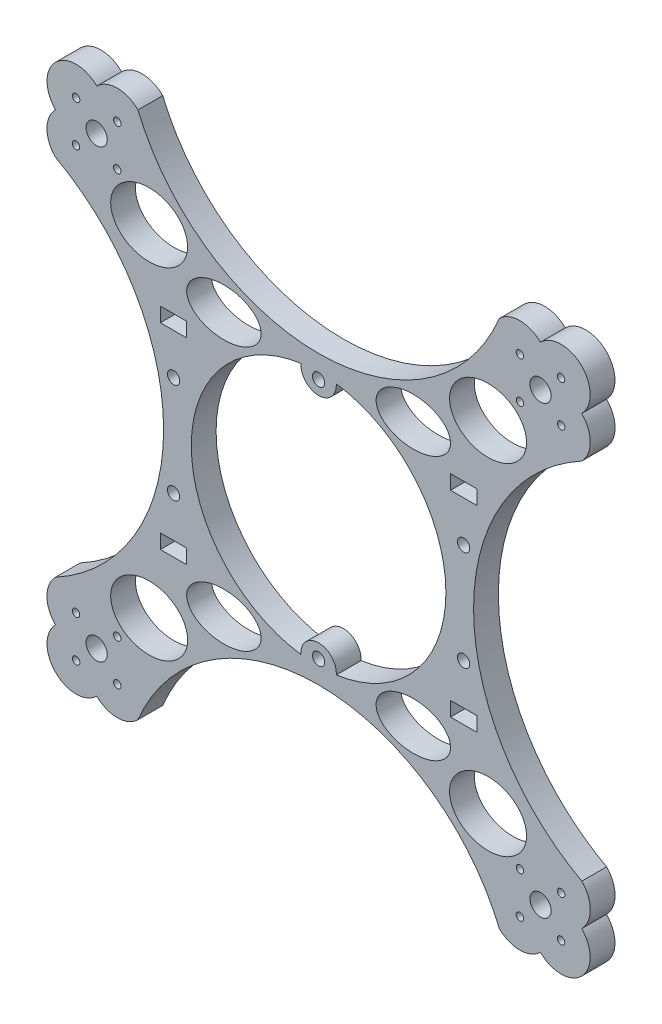
SolidWorks part; units mm, degrees
ref_plane "Front Plane" through (0, 0, 0) normal (0, 0, 1) x (1, 0, 0)
ref_plane "Top Plane" through (0, 0, 0) normal (0, 1, 0) x (1, 0, 0)
ref_plane "Right Plane" through (0, 0, 0) normal (1, 0, 0) x (0, 0, -1)
sketch "Sketch1" plane through (0, 0, 0) normal (0, 0, 1) x (1, 0, 0)
  line L0 (648.4625, 450.3527) -> (648.4625, 50450.3527) construction
  line L1 (648.4625, 450.3527) -> (-34623.3591, 35889.0124) construction
  line L2 (591.254, 498.0985) -> (586.3875, 493.2548) construction
  line L3 (600.9872, 507.7858) -> (605.8538, 512.6295) construction
  line L4 (591.277, 507.8087) -> (596.1435, 512.6524) construction
  line L5 (591.277, 507.8087) -> (586.4104, 502.9651) construction
  line L6 (596.1206, 502.9421) -> (600.9643, 498.0756) construction
  line L7 (596.1206, 502.9421) -> (591.254, 498.0985) construction
  line L8 (596.1206, 502.9421) -> (591.277, 507.8087) construction
  line L9 (596.1206, 502.9421) -> (600.9872, 507.7858) construction
  line L10 (617.3488, 471.8132) -> (617.3488, 475.2133)
  line L11 (611.1488, 471.8132) -> (617.3488, 471.8132)
  line L12 (611.1488, 475.2133) -> (611.1488, 471.8132)
  line L13 (617.3488, 475.2133) -> (611.1488, 475.2133)
  line L14 (617.3488, 471.8132) -> (617.3488, 475.2133)
  line L15 (611.1488, 471.8132) -> (617.3488, 471.8132)
  line L16 (611.1488, 475.2133) -> (611.1488, 471.8132)
  line L17 (617.3488, 475.2133) -> (611.1488, 475.2133)
  line L18 (679.5762, 475.2133) -> (685.7762, 475.2133)
  line L19 (685.7762, 475.2133) -> (685.7762, 471.8132)
  line L20 (685.7762, 471.8132) -> (679.5762, 471.8132)
  line L21 (679.5762, 471.8132) -> (679.5762, 475.2133)
  line L22 (679.5762, 475.2133) -> (685.7762, 475.2133)
  line L23 (685.7762, 475.2133) -> (685.7762, 471.8132)
  line L24 (685.7762, 471.8132) -> (679.5762, 471.8132)
  line L25 (679.5762, 471.8132) -> (679.5762, 475.2133)
  line L26 (705.6709, 402.6069) -> (710.5375, 407.4506) construction
  line L27 (695.9378, 392.9196) -> (691.0712, 388.0759) construction
  line L28 (705.648, 392.8967) -> (700.7814, 388.053) construction
  line L29 (705.648, 392.8967) -> (710.5146, 397.7404) construction
  line L30 (700.8043, 397.7633) -> (695.9607, 402.6299) construction
  line L31 (700.8043, 397.7633) -> (705.6709, 402.6069) construction
  line L32 (700.8043, 502.9421) -> (695.9378, 507.7858) construction
  line L33 (648.4625, 450.3527) -> (35920.2841, 35889.0124) construction
  line L34 (700.8043, 502.9421) -> (705.648, 507.8087) construction
  line L35 (700.8043, 502.9421) -> (705.6709, 498.0985) construction
  line L36 (-351.5375, 450.3527) -> (49648.4625, 450.3527) construction
  line L37 (700.8043, 397.7633) -> (705.648, 392.8967) construction
  line L38 (700.8043, 502.9421) -> (695.9607, 498.0756) construction
  line L39 (705.648, 507.8087) -> (710.5146, 502.9651) construction
  line L40 (705.648, 507.8087) -> (700.7814, 512.6524) construction
  line L41 (695.9378, 507.7858) -> (691.0712, 512.6295) construction
  line L42 (705.6709, 498.0985) -> (710.5375, 493.2548) construction
  line L43 (700.8043, 397.7633) -> (695.9378, 392.9196) construction
  line L44 (596.1206, 397.7633) -> (600.9872, 392.9196) construction
  line L45 (596.1206, 397.7633) -> (591.277, 392.8967) construction
  line L46 (596.1206, 397.7633) -> (591.254, 402.6069) construction
  line L47 (596.1206, 397.7633) -> (600.9643, 402.6299) construction
  line L48 (591.277, 392.8967) -> (586.4104, 397.7404) construction
  line L49 (591.277, 392.8967) -> (596.1435, 388.053) construction
  line L50 (600.9872, 392.9196) -> (605.8538, 388.0759) construction
  line L51 (591.254, 402.6069) -> (586.3875, 407.4506) construction
  line L52 (679.5762, 428.8922) -> (679.5762, 425.4922)
  line L53 (685.7762, 428.8922) -> (679.5762, 428.8922)
  line L54 (685.7762, 425.4922) -> (685.7762, 428.8922)
  line L55 (679.5762, 425.4922) -> (685.7762, 425.4922)
  line L56 (679.5762, 428.8922) -> (679.5762, 425.4922)
  line L57 (685.7762, 428.8922) -> (679.5762, 428.8922)
  line L58 (685.7762, 425.4922) -> (685.7762, 428.8922)
  line L59 (679.5762, 425.4922) -> (685.7762, 425.4922)
  line L60 (617.3488, 425.4922) -> (611.1488, 425.4922)
  line L61 (611.1488, 425.4922) -> (611.1488, 428.8922)
  line L62 (611.1488, 428.8922) -> (617.3488, 428.8922)
  line L63 (617.3488, 428.8922) -> (617.3488, 425.4922)
  line L64 (617.3488, 425.4922) -> (611.1488, 425.4922)
  line L65 (611.1488, 425.4922) -> (611.1488, 428.8922)
  line L66 (611.1488, 428.8922) -> (617.3488, 428.8922)
  line L67 (617.3488, 428.8922) -> (617.3488, 425.4922)
  arc A0 (652.6297, 480.0867) -> (678.487, 450.3527) centre (648.4625, 450.3527) cw
  circle A1 centre (648.4625, 478.8805) radius 1.4499
  arc A2 (586.3875, 493.2548) -> (586.3875, 407.4506) centre (563.0938, 450.3527) cw
  arc A3 (586.4104, 502.9651) -> (586.3875, 493.2548) centre (591.254, 498.0985) ccw
  arc A4 (596.1435, 512.6524) -> (605.8538, 512.6295) centre (600.9872, 507.7858) cw
  arc A5 (586.4104, 502.9651) -> (596.1435, 512.6524) centre (591.277, 507.8087) cw
  circle A6 centre (682.6609, 462.1663) radius 1.4499
  arc A7 (652.6297, 480.0867) -> (648.4625, 475.6107) centre (648.4625, 479.7886) cw
  circle A8 centre (600.9643, 498.0756) radius 0.8749
  circle A9 centre (591.254, 498.0985) radius 0.8749
  circle A10 centre (591.277, 507.8087) radius 0.8749
  circle A11 centre (600.9872, 507.7858) radius 0.8749
  circle A12 centre (596.1206, 502.9421) radius 2.4999
  arc A13 (644.2953, 480.0867) -> (648.4625, 475.6107) centre (648.4625, 479.7886) ccw
  circle A14 centre (700.8043, 502.9421) radius 2.4999
  circle A15 centre (695.9378, 507.7858) radius 0.8749
  circle A16 centre (705.648, 507.8087) radius 0.8749
  circle A17 centre (705.6709, 498.0985) radius 0.8749
  circle A18 centre (695.9607, 498.0756) radius 0.8749
  arc A19 (710.5146, 502.9651) -> (700.7814, 512.6524) centre (705.648, 507.8087) ccw
  arc A20 (700.7814, 512.6524) -> (691.0712, 512.6295) centre (695.9378, 507.7858) ccw
  arc A21 (710.5146, 502.9651) -> (710.5375, 493.2548) centre (705.6709, 498.0985) cw
  arc A22 (605.8538, 512.6295) -> (691.0712, 512.6295) centre (648.4625, 530.3427) ccw
  arc A23 (710.5375, 493.2548) -> (710.5375, 407.4506) centre (733.8311, 450.3527) ccw
  circle A24 centre (614.264, 462.1663) radius 1.4499
  arc A25 (644.2953, 480.0867) -> (618.4379, 450.3527) centre (648.4625, 450.3527) ccw
  arc A26 (644.2953, 420.6188) -> (618.4379, 450.3527) centre (648.4625, 450.3527) cw
  circle A27 centre (614.264, 438.5391) radius 1.4499
  arc A28 (605.8538, 388.0759) -> (691.0712, 388.0759) centre (648.4625, 370.3627) cw
  arc A29 (710.5146, 397.7404) -> (710.5375, 407.4506) centre (705.6709, 402.6069) ccw
  arc A30 (700.7814, 388.053) -> (691.0712, 388.0759) centre (695.9378, 392.9196) cw
  arc A31 (710.5146, 397.7404) -> (700.7814, 388.053) centre (705.648, 392.8967) cw
  circle A32 centre (695.9607, 402.6299) radius 0.8749
  circle A33 centre (705.6709, 402.6069) radius 0.8749
  circle A34 centre (705.648, 392.8967) radius 0.8749
  circle A35 centre (695.9378, 392.9196) radius 0.8749
  circle A36 centre (700.8043, 397.7633) radius 2.4999
  arc A37 (644.2953, 420.6188) -> (648.4625, 425.0947) centre (648.4625, 420.9168) cw
  circle A38 centre (596.1206, 397.7633) radius 2.4999
  circle A39 centre (600.9872, 392.9196) radius 0.8749
  circle A40 centre (591.277, 392.8967) radius 0.8749
  circle A41 centre (591.254, 402.6069) radius 0.8749
  circle A42 centre (600.9643, 402.6299) radius 0.8749
  arc A43 (652.6297, 420.6188) -> (648.4625, 425.0947) centre (648.4625, 420.9168) ccw
  circle A44 centre (682.6609, 438.5391) radius 1.4499
  arc A45 (586.4104, 397.7404) -> (596.1435, 388.053) centre (591.277, 392.8967) ccw
  arc A46 (596.1435, 388.053) -> (605.8538, 388.0759) centre (600.9872, 392.9196) ccw
  arc A47 (586.4104, 397.7404) -> (586.3875, 407.4506) centre (591.254, 402.6069) cw
  circle A48 centre (648.4625, 421.8249) radius 1.4499
  arc A49 (652.6297, 420.6188) -> (678.487, 450.3527) centre (648.4625, 450.3527) ccw
  ellipse E0 centre (608.4968, 490.5075) end of major axis (617.5697, 490.5075) minor radius 7.5681
  ellipse E1 centre (670.7988, 481.4263) end of major axis (662.0214, 481.4263) minor radius 5.6013
  ellipse E2 centre (688.4282, 490.5075) end of major axis (679.3553, 490.5075) minor radius 7.5681
  ellipse E3 centre (626.1261, 481.4263) end of major axis (634.9035, 481.4263) minor radius 5.6013
  ellipse E4 centre (626.1261, 419.2791) end of major axis (634.9035, 419.2791) minor radius 5.6013
  ellipse E5 centre (688.4282, 410.1979) end of major axis (679.3553, 410.1979) minor radius 7.5681
  ellipse E6 centre (670.7988, 419.2791) end of major axis (662.0214, 419.2791) minor radius 5.6013
  ellipse E7 centre (608.4968, 410.1979) end of major axis (617.5697, 410.1979) minor radius 7.5681
extrude "Boss-Extrude3" add sketch "Sketch1" along normal blind 5.85
